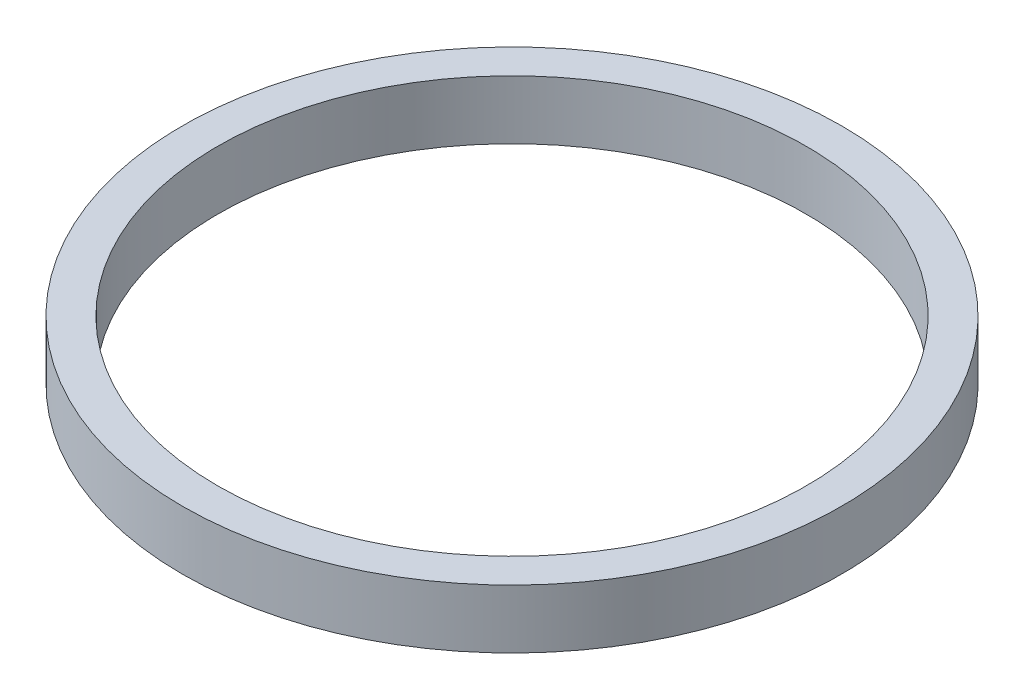
SolidWorks part; units mm, degrees
ref_plane "Front Plane" through (0, 0, 0) normal (0, 0, 1) x (1, 0, 0)
ref_plane "Top Plane" through (0, 0, 0) normal (0, 1, 0) x (1, 0, 0)
ref_plane "Right Plane" through (0, 0, 0) normal (1, 0, 0) x (0, 0, -1)
sketch "Sketch1" plane through (0, 0, 0) normal (0, 1, 0) x (1, 0, 0)
  circle A0 centre (0, 0) radius 14
  circle A1 centre (0, 0) radius 12.5
  dimension "D1" = 28
  dimension "D2" = 25
extrude "Boss-Extrude1" add sketch "Sketch1" along normal blind 2.5
equation "\"2.5.00mm\"=10"
